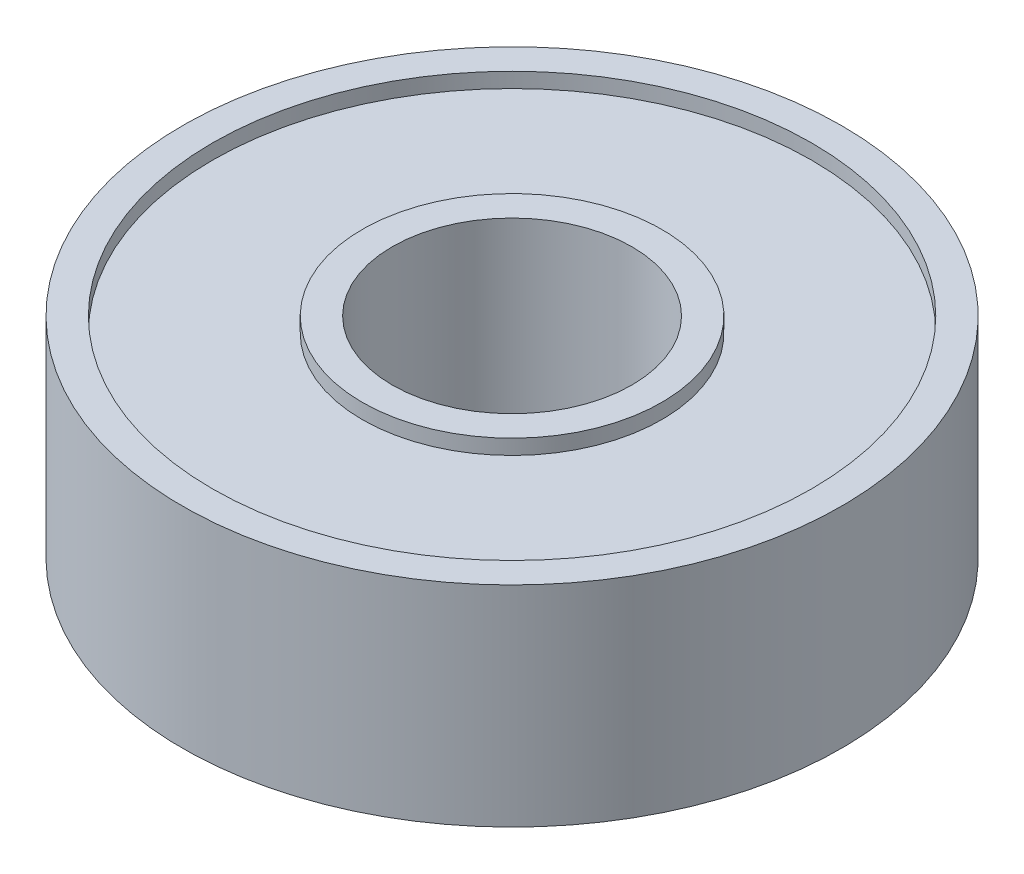
SolidWorks part; units mm, degrees
material "1060 Alloy"
ref_plane "Front Plane" through (0, 0, 0) normal (0, 0, 1) x (1, 0, 0)
ref_plane "Top Plane" through (0, 0, 0) normal (0, 1, 0) x (1, 0, 0)
ref_plane "Right Plane" through (0, 0, 0) normal (1, 0, 0) x (0, 0, -1)
sketch "Sketch1" plane through (0, 0, 0) normal (0, 1, 0) x (1, 0, 0)
  circle A0 centre (0, 0) radius 4
  circle A1 centre (0, 0) radius 11
  dimension "D1" = 8
  dimension "D2" = 22
extrude "Boss-Extrude1" add sketch "Sketch1" along normal blind 7
sketch "Sketch2" plane through (0, 7, 0) normal (0, 1, 0) x (1, 0, 0)
  circle A0 centre (0, 0) radius 5
  circle A1 centre (0, 0) radius 10
  dimension "D1" = 10
  dimension "D2" = 20
extrude "Cut-Extrude1" cut sketch "Sketch2" against normal blind 0.5
ref_plane "Plane1" through (0, 3.5, 0) normal (0, 1, 0) x (1, 0, 0)
mirror "Mirror1" about plane through (0, 3.5, 0) normal (0, 1, 0) of "Cut-Extrude1"
